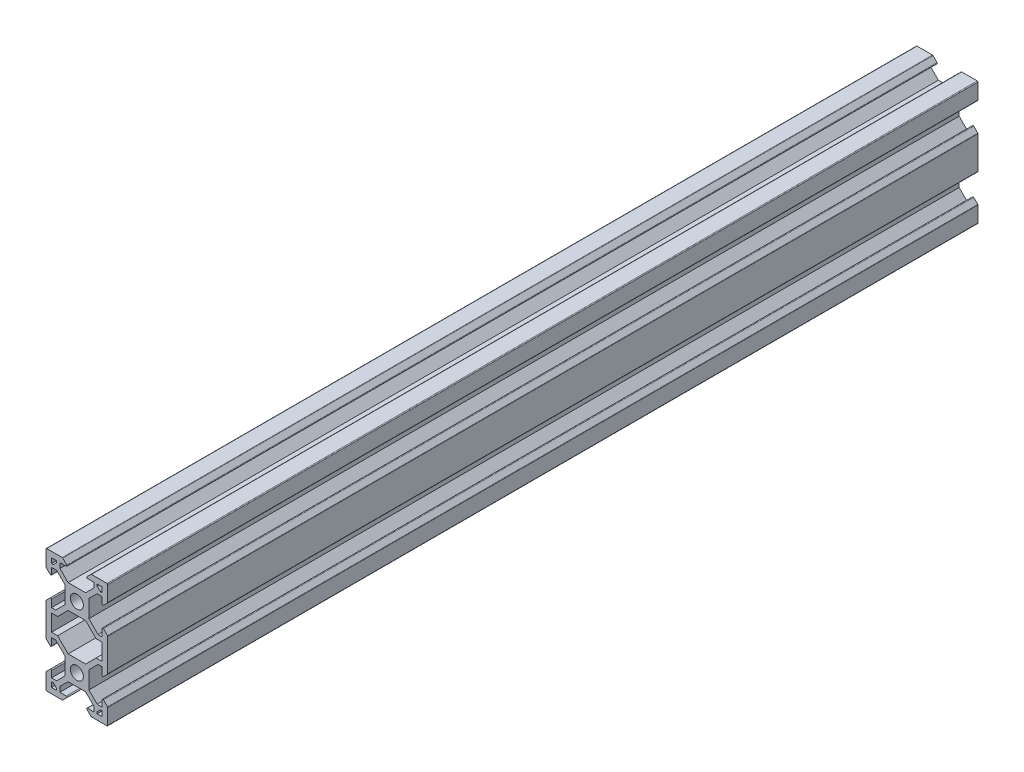
SolidWorks part; units mm, degrees
material "1060 Alloy"
ref_plane "Front Plane" through (0, 0, 0) normal (0, 0, 1) x (1, 0, 0)
ref_plane "Top Plane" through (0, 0, 0) normal (0, 1, 0) x (1, 0, 0)
ref_plane "Right Plane" through (0, 0, 0) normal (1, 0, 0) x (0, 0, -1)
sketch "Sketch1" plane through (0, 0, 0) normal (0, 0, 1) x (1, 0, 0)
  line L0 (8.2, -10) -> (10, -10)
  line L2 (10, -10) -> (10, -4.64)
  line L3 (10, -4.64) -> (8.2, -2.84)
  line L4 (8.2, -2.84) -> (8.2, -5.8007)
  line L5 (8.2, -5.8007) -> (6.8613, -5.8007)
  line L6 (6.8613, -5.8007) -> (3.9007, -2.84)
  line L7 (3.9007, -2.84) -> (3.9007, 2.84)
  line L8 (3.9007, 2.84) -> (6.56, 5.4993)
  line L9 (6.56, 5.4993) -> (8.2, 5.4993)
  line L10 (8.2, 5.4993) -> (8.2, 2.84)
  line L11 (8.2, 2.84) -> (10, 4.64)
  line L12 (10, 4.64) -> (10, 10)
  line L13 (10, 10) -> (4.64, 10)
  line L14 (4.64, 10) -> (2.84, 8.2)
  line L15 (2.84, 8.2) -> (5.4993, 8.2)
  line L16 (5.4993, 8.2) -> (5.4993, 6.56)
  line L17 (5.4993, 6.56) -> (2.84, 3.9007)
  line L18 (2.84, 3.9007) -> (-2.84, 3.9007)
  line L19 (-2.84, 3.9007) -> (-5.4993, 6.56)
  line L20 (-5.4993, 6.56) -> (-5.4993, 8.2)
  line L21 (-5.4993, 8.2) -> (-2.84, 8.2)
  line L22 (-2.84, 8.2) -> (-4.64, 10)
  line L23 (-4.64, 10) -> (-10, 10)
  line L24 (-10, 10) -> (-10, 4.64)
  line L25 (-10, 4.64) -> (-8.2, 2.84)
  line L26 (-8.2, 2.84) -> (-8.2, 5.4993)
  line L27 (-8.2, 5.4993) -> (-6.56, 5.4993)
  line L28 (-6.56, 5.4993) -> (-3.9007, 2.84)
  line L29 (-3.9007, 2.84) -> (-3.9007, -2.84)
  line L30 (-3.9007, -2.84) -> (-6.8613, -5.8007)
  line L31 (-6.8613, -5.8007) -> (-8.2, -5.8007)
  line L32 (-8.2, -5.8007) -> (-8.2, -2.84)
  line L33 (-8.2, -2.84) -> (-10, -4.64)
  line L34 (-10, -4.64) -> (-10, -10)
  line L64 (8.2, -7.3007) -> (8.2, -10)
  line L70 (-8.2, -10) -> (-8.2, -7.3007)
  line L71 (-8.2, -7.3007) -> (-6.24, -7.3007)
  line L72 (-6.24, -7.3007) -> (-2.84, -3.9007)
  line L73 (-2.84, -3.9007) -> (2.84, -3.9007)
  line L74 (2.84, -3.9007) -> (6.24, -7.3007)
  line L75 (6.24, -7.3007) -> (8.2, -7.3007)
  line L76 (-10, -10) -> (-8.2, -10)
  circle A0 centre (0, 0) radius 2.1
  point P46 (0, -3.9007)
  point P47 (0, 3.9007)
  point P49 (-3.9007, 0)
  point P50 (3.9007, 0)
  dimension "D1" = 4.2
  dimension "D8" = 1.8
  dimension "D2" = 20
  dimension "D3" = 20
  dimension "D4" = 5.68
  dimension "D5" = 90
  dimension "D6" = 10
  dimension "D7" = 10
  dimension "D9" = 1.8
  dimension "D10" = 1.8
  dimension "D11" = 1.5
  dimension "D12" = 1.5
  dimension "D13" = 1.64
  dimension "D14" = 1.5
  dimension "D15" = 1.96
extrude "Boss-Extrude2" add sketch "Sketch1" along normal blind 282
sketch "Sketch2" plane through (0, 0, 282) normal (0, 0, 1) x (1, 0, 0)
  line L0 (-8.2, 2.84) -> (-8.2, 5.4993) construction
  line L1 (-5.4993, 8.2) -> (-2.84, 8.2) construction
  line L2 (-8.2, 6.5693) -> (-8.2, 8.2)
  line L3 (-8.2, 8.2) -> (-6.5693, 8.2)
  line L4 (8.2, 5.4993) -> (8.2, 2.84) construction
  line L5 (8.2, 8.2) -> (8.2, 6.5693)
  line L6 (3.9007, 2.84) -> (6.56, 5.4993) construction
  line L7 (-5.4993, 6.56) -> (-5.4993, 8.2) construction
  line L8 (6.56, 5.4993) -> (8.2, 5.4993) construction
  line L11 (6.5693, 8.2) -> (6.5693, 6.56)
  line L12 (6.5693, 8.2) -> (6.5693, 7.63)
  line L16 (6.5693, 8.2) -> (8.2, 8.2)
  line L17 (-8.2, 6.5693) -> (-6.56, 6.5693)
  line L18 (-8.2, 6.5693) -> (-7.63, 6.5693)
  line L19 (-7.63, 6.5693) -> (-6.5693, 7.63)
  line L20 (6.5693, 7.63) -> (7.63, 6.5693)
  line L22 (7.63, 6.5693) -> (8.2, 6.5693)
  line L24 (-6.5693, 7.63) -> (-6.5693, 8.2)
  dimension "D5" = 1.5
  dimension "D1" = 1.07
  dimension "D3" = 1.07
  dimension "D2" = 1.07
  dimension "D4" = 1.07
extrude "Cut-Extrude1" cut sketch "Sketch2" against normal through all
fillet "Fillet1" radius 0.25 14 edges at (8.2, 2.84, 141) (-10, 4.64, 141) (-4.64, 10, 141) (4.64, 10, 141) (-10, -4.64, 141) (-10, 10, 141) (10, -4.64, 141) (10, 10, 141) (8.2, -2.84, 141) (-8.2, -2.84, 141) (-8.2, 2.84, 141) (10, 4.64, 141) (2.84, 8.2, 141) (-2.84, 8.2, 141)
ref_plane "Plane1" through (0, -10, 0) normal (0, -1, 0) x (-1, 0, 0)
mirror "Mirror1" about plane through (0, -10, 0) normal (0, -1, 0) of "Fillet1", "Boss-Extrude2"
mirror "Mirror2" about plane through (0, -10, 0) normal (0, -1, 0) of "Cut-Extrude1"
